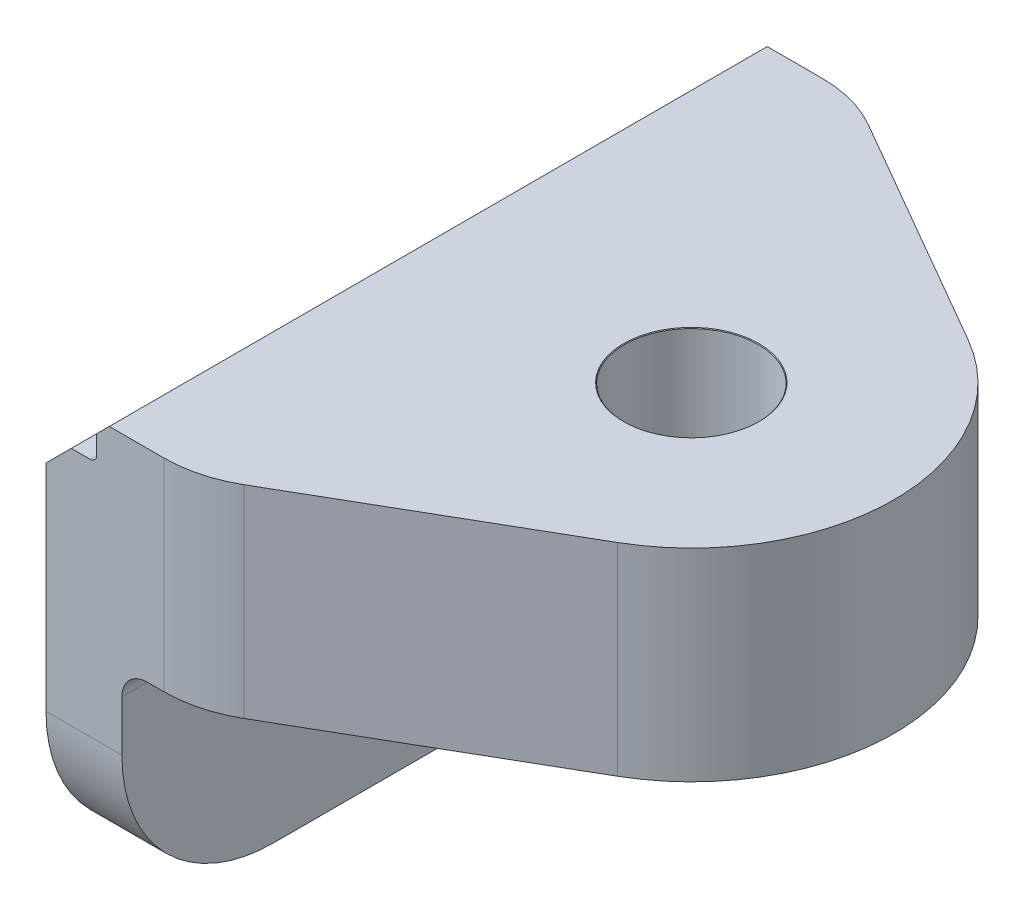
SolidWorks part; units mm, degrees
material "6061 Alloy"
ref_plane "Front Plane" through (0, 0, 0) normal (0, 0, 1) x (1, 0, 0)
ref_plane "Top Plane" through (0, 0, 0) normal (0, 1, 0) x (1, 0, 0)
ref_plane "Right Plane" through (0, 0, 0) normal (1, 0, 0) x (0, 0, -1)
sketch "Sketch1" plane through (0, 0, 0) normal (0, 1, 0) x (1, 0, 0)
  line L0 (0, 0) -> (0, 13)
  line L1 (0, 13) -> (3, 13)
  line L2 (3, 13) -> (25.5167, 0)
  line L3 (25.5167, 0) -> (3, -13)
  line L4 (3, -13) -> (0, -13)
  line L5 (0, -13) -> (0, 0)
  dimension "D1" = 26
  dimension "D2" = 60
  dimension "D3" = 150
  dimension "D4" = 3
extrude "Boss-Extrude1" add sketch "Sketch1" along normal mid plane 8
fillet "Fillet1" radius 8 1 edges at (25.5167, 0, 0)
ref_plane "Plane1" through (0, 2.5, 0) normal (0, 1, 0) x (1, 0, 0)
sketch "Sketch7" plane through (0, 2.5, 0) normal (0, 1, 0) x (1, 0, 0)
  line L1 (0, 13) -> (-3, 13)
  line L2 (0, 13) -> (0, -13)
  line L3 (0, -13) -> (-3, -13)
  line L4 (-3, 13) -> (-3, -13)
  dimension "D1" = 26
  dimension "D2" = 3
  dimension "D3" = 0
  dimension "D4" = 13
extrude "Boss-Extrude3" add sketch "Sketch7" against normal blind 15.5
hole_wizard "M3x0.5 Tapped Hole1" positions "Sketch8" profile "Sketch9" tap size "M3x0.5" standard "ANSI Metric"
sketch "Sketch8" plane through (-3, 0, 0) normal (-1, 0, 0) x (0, 0, 1)
  line L1 (9.0842, 2.5) -> (-9.0842, 2.5) construction
  line L2 (-13, -13) -> (-13, 2.5) construction
  line L3 (13, -13) -> (13, 2.5) construction
  point P0 (9.5, -1)
  point P2 (-9.5, -1)
  dimension "D1" = 3.5
  dimension "D2" = 3.5
  dimension "D3" = 3.5
  dimension "D4" = 3.5
sketch "Sketch9" plane through (-3, -1, 9.5) normal (0, 1, 0) x (0, 0, 1)
  line L0 (0, 0) -> (0, 8.2511)
  line L1 (0, 8.2511) -> (1.25, 7.5)
  line L2 (1.25, 7.5) -> (1.25, 0)
  line L5 (1.25, 0) -> (0, 0)
  line L10 (0, 8.2511) -> (-1.25, 7.5) construction
  line L11 (0, -6.35) -> (0, 107.95) construction
  dimension "Tap Drill Dia." = 2.5
  dimension "Tap Drill Depth" = 7.5
  dimension "Drill Angle" = 118
hole_wizard "M3 Clearance Hole2" positions "Sketch10" profile "Sketch11" hole size "M3" standard "ANSI Metric" end condition through all
sketch "Sketch10" plane through (-3, 0, 0) normal (-1, 0, 0) x (0, 0, 1)
  line L0 (-13, -13) -> (-13, 2.5) construction
  line L1 (13, -13) -> (13, 2.5) construction
  line L2 (-13, -13) -> (13, -13) construction
  point P0 (-5, -8)
  point P2 (5, -8)
  dimension "D1" = 8
  dimension "D2" = 8
  dimension "D3" = 5
  dimension "D4" = 5
sketch "Sketch11" plane through (-3, -8, -5) normal (0, 1, 0) x (0, 0, 1)
  line L0 (0, 0) -> (0, 20.5167)
  line L1 (0, 20.5167) -> (1.7, 20.5167)
  line L2 (1.7, 20.5167) -> (1.7, 0)
  line L5 (1.7, 0) -> (0, 0)
  line L11 (0, -6.35) -> (0, 107.95) construction
  dimension "Thru Hole Dia." = 3.4
  dimension "Thru Hole Depth" = 20.5167
sketch "Sketch12" plane through (0, 4, 0) normal (0, 1, 0) x (1, 0, 0)
  line L1 (0, -13) -> (-1, -13)
  line L2 (0, -13) -> (0, 13)
  line L3 (0, 13) -> (-1, 13)
  line L4 (-1, -13) -> (-1, 13)
  dimension "D1" = 1
extrude "Boss-Extrude4" add sketch "Sketch12" against normal blind 2
hole_wizard "CBORE for M5 SHCS1" positions "Sketch18" profile "Sketch20" counterbore size "M5" standard "ANSI Metric" end condition through all
sketch "Sketch18" plane through (0, -4, 0) normal (0, -1, 0) x (-1, 0, 0)
  line L0 (0, -13) -> (0, 13) construction
  line L3 (0, 0) -> (-21.7361, 0) construction
  point P0 (-9.5, 0)
  dimension "D1" = 9.5
sketch "Sketch20" plane through (9.5, -4, 0) normal (1, 0, 0) x (0, 0, -1)
  line L0 (0, 0) -> (0, 8)
  line L1 (2.65, 7.975) -> (2.675, 8)
  line L2 (2.65, 7.975) -> (2.65, 4.025)
  line L3 (2.65, 4.025) -> (2.675, 4)
  line L4 (2.675, 4) -> (5, 4)
  line L5 (5, 4) -> (5, 0)
  line L7 (5, 0) -> (0, 0)
  line L9 (-2.65, 4.025) -> (-2.675, 4) construction
  line L11 (0, -6.35) -> (0, 107.95) construction
  line L12 (2.675, 8) -> (0, 8)
  line L13 (-2.65, 7.975) -> (-2.675, 8) construction
  dimension "Thru Hole Dia." = 5.3
  dimension "Thru Hole Depth" = 8
  dimension "C'Bore Dia." = 10
  dimension "C'Bore Depth" = 4
  dimension "Mid C'Sink Dia." = 5.35
  dimension "Mid C'Sink Angle" = 90
  dimension "Far C'Sink Dia." = 5.35
  dimension "Far C'Sink Angle" = 90
fillet "Fillet4" radius 6 2 edges at (-1.5, -13, 13) (-1.5, -13, -13)
fillet "Fillet5" radius 1 1 edges at (0, -4, 0)
fillet "Fillet6" radius 5 2 edges at (3, 0, -13) (3, 0, 13)
fillet "Fillet7" radius 0.25 1 edges at (-1, 2.5, 0)
chamfer "Chamfer1" distance 1 1 edges at (-3, 2.5, 0)
chamfer "Chamfer2" distance 0.5 angle 45 1 edges at (-1, 4, 0)
